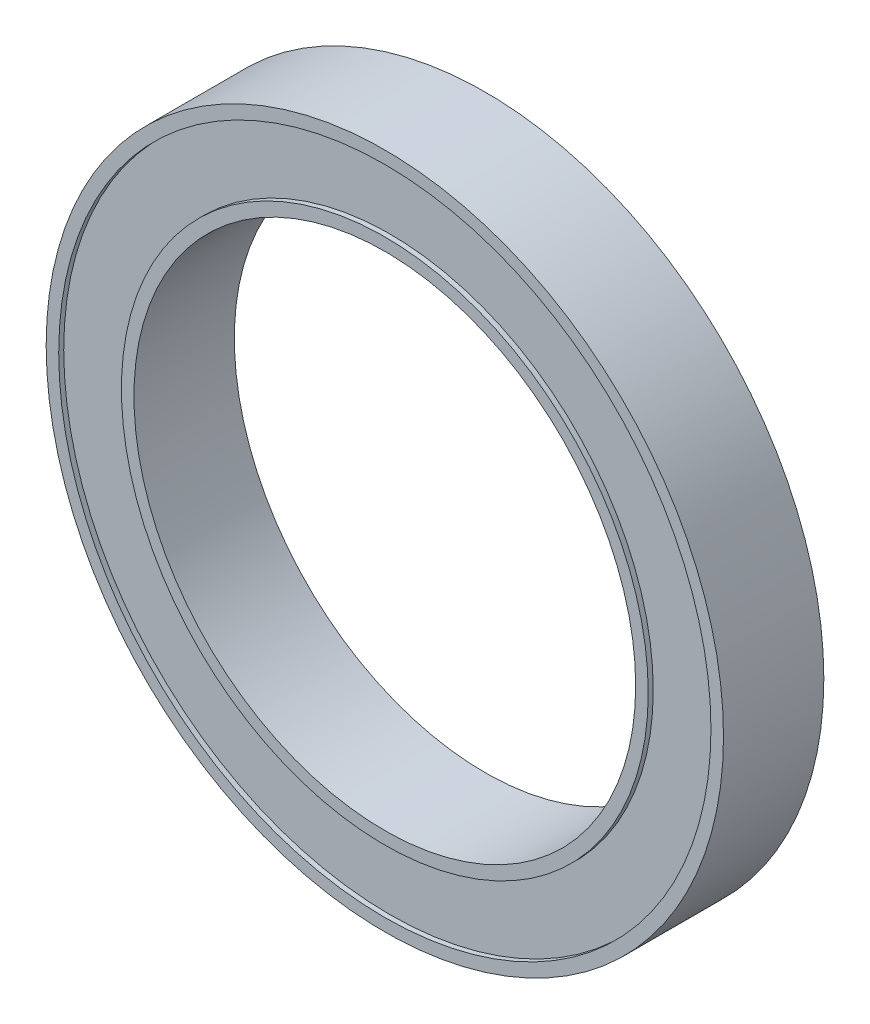
SolidWorks part; units mm, degrees
ref_plane "Front Plane" through (0, 0, 0) normal (0, 0, 1) x (1, 0, 0)
ref_plane "Top Plane" through (0, 0, 0) normal (0, 1, 0) x (1, 0, 0)
ref_plane "Right Plane" through (0, 0, 0) normal (1, 0, 0) x (0, 0, -1)
ref_plane "Plane1"
sketch "Sketch1" plane through (0, 0, 0) normal (0, 0, 1) x (1, 0, 0)
  circle A0 centre (0, 0) radius 13.5
  circle A1 centre (0, 0) radius 13
  circle A2 centre (0, 0) radius 10.5
  circle A3 centre (0, 0) radius 10
  dimension "D1" = 27
  dimension "D2" = 20
extrude "Extrusion1" add sketch "Sketch1" along normal blind 4 contours A2 A3 | A0 A1
ref_plane "Plane2"
sketch "Sketch2" plane through (0, 0, 0.2) normal (0, 0, 1) x (1, 0, 0)
  circle A0 centre (0, 0) radius 13
  circle A1 centre (0, 0) radius 10.5
extrude "Extrusion2" add sketch "Sketch2" along normal blind 3.6 contours A0 A1
